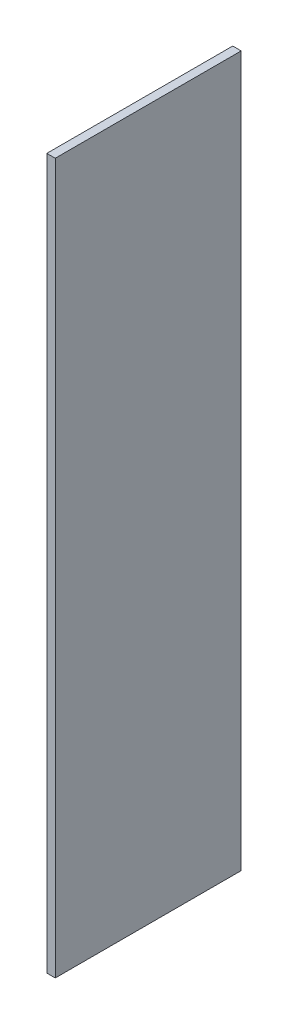
SolidWorks part; units mm, degrees
ref_plane "Front Plane" through (0, 0, 0) normal (0, 0, 1) x (1, 0, 0)
ref_plane "Top Plane" through (0, 0, 0) normal (0, 1, 0) x (1, 0, 0)
ref_plane "Right Plane" through (0, 0, 0) normal (1, 0, 0) x (0, 0, -1)
sketch "Sketch2" plane through (0, 0, 0) normal (0, 1, 0) x (1, 0, 0)
  line L1 (-12.7, -279.4) -> (12.7, -279.4)
  line L2 (-12.7, -279.4) -> (-12.7, 279.4)
  line L3 (-12.7, 279.4) -> (12.7, 279.4)
  line L4 (12.7, -279.4) -> (12.7, 279.4)
  line L5 (-12.7, -279.4) -> (12.7, 279.4) construction
  line L6 (-12.7, 279.4) -> (12.7, -279.4) construction
  point P0 (0, 0)
extrude "Boss-Extrude1" add sketch "Sketch2" along normal blind 2133.6
